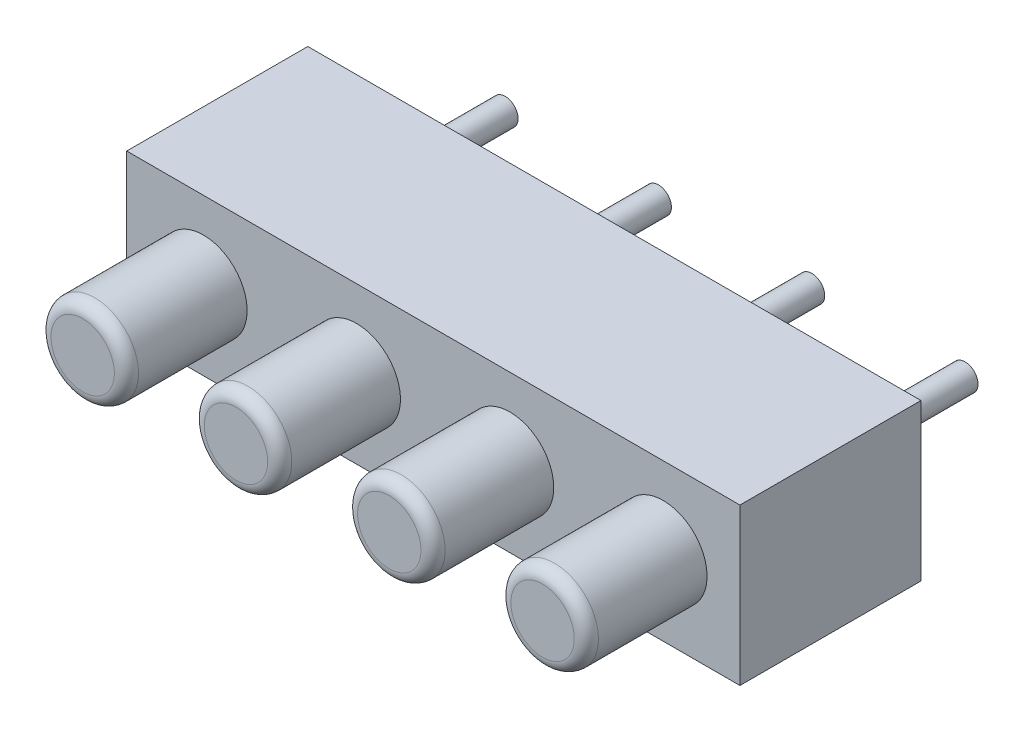
SolidWorks part; units mm, degrees
ref_plane "Спереди" through (0, 0, 0) normal (0, 0, 1) x (1, 0, 0)
ref_plane "Сверху" through (0, 0, 0) normal (0, 1, 0) x (1, 0, 0)
ref_plane "Справа" through (0, 0, 0) normal (1, 0, 0) x (0, 0, -1)
sketch "Эскиз1" plane through (0, 0, 0) normal (0, 0, 1) x (1, 0, 0)
  line L1 (0, 0) -> (10.16, 0)
  line L2 (0, 0) -> (0, 2.59)
  line L3 (0, 2.59) -> (10.16, 2.59)
  line L4 (10.16, 0) -> (10.16, 2.59)
  dimension "D1" = 10.16
  dimension "D2" = 2.59
extrude "Бобышка-Вытянуть1" add sketch "Эскиз1" along normal blind 3
sketch "Эскиз2" plane through (0, 0, 3) normal (0, 0, 1) x (1, 0, 0)
  line L0 (0, 1.295) -> (10.16, 1.295) construction
  line L1 (0, 2.59) -> (0, 0) construction
  line L2 (10.16, 0) -> (10.16, 2.59) construction
  circle A0 centre (1.27, 1.295) radius 0.725
  circle A1 centre (3.81, 1.295) radius 0.725
  circle A2 centre (6.35, 1.295) radius 0.725
  circle A3 centre (8.89, 1.295) radius 0.725
  point P14 (5.08, 1.295)
  dimension "D1" = 1.45
  dimension "D2" = 1.45
  dimension "D3" = 1.45
  dimension "D4" = 1.45
  dimension "D5" = 2.54
  dimension "D6" = 2.54
  dimension "D7" = 2.54
  dimension "D8" = 1.27
extrude "Бобышка-Вытянуть2" add sketch "Эскиз2" along normal offset from surface (2 mm away) 5 up to face at (5.08, 1.295, 0)
sketch "Эскиз3" plane through (0, 0, 0) normal (0, 0, -1) x (-1, 0, 0)
  circle A0 centre (-1.27, 1.295) radius 0.215
  circle A1 centre (-3.81, 1.295) radius 0.215
  circle A2 centre (-6.35, 1.295) radius 0.215
  circle A3 centre (-8.89, 1.295) radius 0.215
  dimension "D1" = 0.43
  dimension "D2" = 0.43
  dimension "D3" = 0.43
  dimension "D4" = 0.43
extrude "Бобышка-Вытянуть3" add sketch "Эскиз3" along normal blind 2
fillet "Скругление1" radius 0.2 4 edges at (0.545, 1.295, 5) (3.085, 1.295, 5) (5.625, 1.295, 5) (8.165, 1.295, 5)
